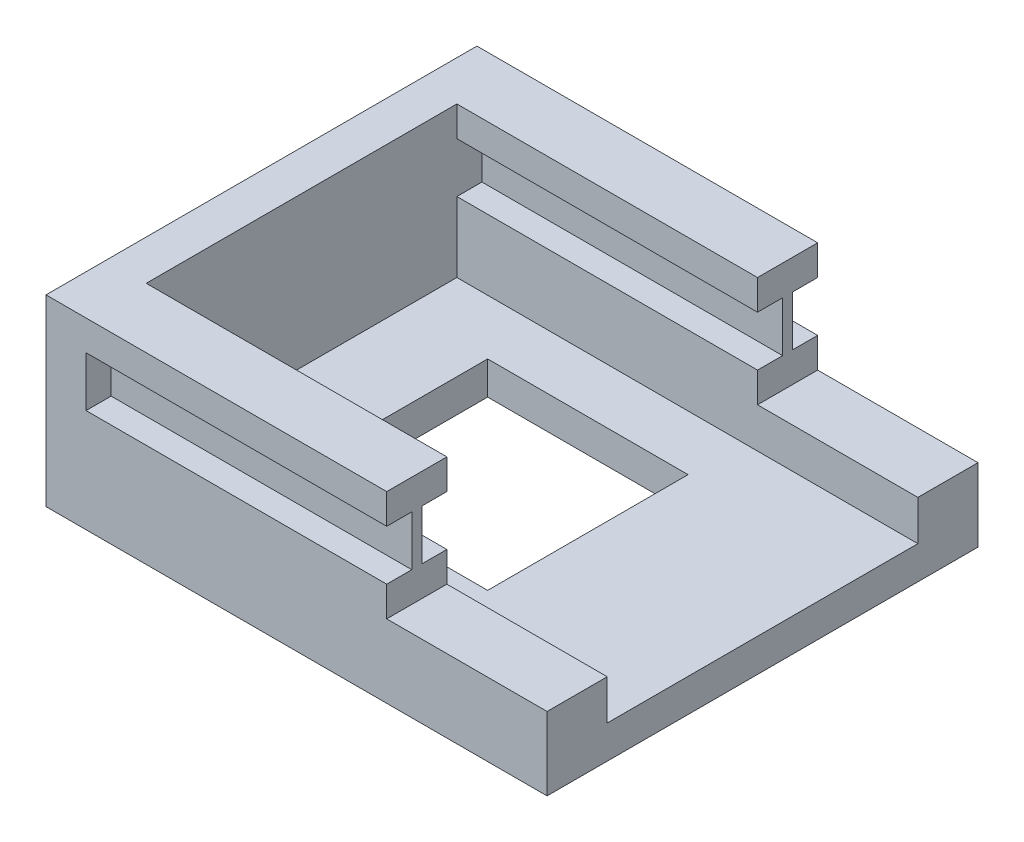
SolidWorks part; units mm, degrees
ref_plane "Front Plane" through (0, 0, 0) normal (0, 0, 1) x (1, 0, 0)
ref_plane "Top Plane" through (0, 0, 0) normal (0, 1, 0) x (1, 0, 0)
ref_plane "Right Plane" through (0, 0, 0) normal (1, 0, 0) x (0, 0, -1)
sketch "Sketch1" plane through (0, 0, 0) normal (0, 0, 1) x (1, 0, 0)
  line L0 (1, 15) -> (5, 15)
  line L1 (1, -3.3) -> (56, -3.3)
  line L2 (1, -3.3) -> (1, 15)
  line L3 (5, 15) -> (5, 4)
  line L4 (5, 4) -> (56, 4)
  line L5 (56, 4) -> (56, -3.3)
  point P1 (0, 0)
  point P4 (0, 0)
  point P8 (0, 0)
  point P9 (0, 0)
  point P10 (0, 0)
  point P11 (0, 0)
  point P12 (0, 0)
  dimension "D1" = 51
  dimension "D2" = 7.3
  dimension "D3" = 11
extrude "Boss-Extrude1" add sketch "Sketch1" along normal blind 43 contours L4 L5 L1 L2 L0 L3
sketch "Sketch3" plane through (0, 0, 43) normal (0, 0, 1) x (1, 0, 0)
  line L0 (56, 4) -> (56, -3.3) construction
  line L1 (5, 4) -> (56, 4)
  line L2 (5, 4) -> (5, 0)
  line L3 (5, 0) -> (56, 0)
  line L4 (56, 4) -> (56, 0)
  dimension "D1" = 4
extrude "Cut-Extrude1" cut sketch "Sketch3" against normal blind 31 from offset 6 offset against normal yes
sketch "Sketch4" plane through (0, 0, 0) normal (0, 1, 0) x (1, 0, 0)
  line L0 (5, -6) -> (5, -37) construction
  line L1 (13.57, -11.5) -> (33.57, -11.5)
  line L2 (13.57, -11.5) -> (13.57, -31.5)
  line L3 (13.57, -31.5) -> (33.57, -31.5)
  line L4 (33.57, -11.5) -> (33.57, -31.5)
  line L5 (13.57, -11.5) -> (33.57, -31.5) construction
  line L6 (13.57, -31.5) -> (33.57, -11.5) construction
  line L7 (1, 0) -> (56, 0) construction
  point P0 (23.57, -21.5)
  dimension "D1" = 20
  dimension "D2" = 20
  dimension "D3" = 8.57
  dimension "D4" = 11.5
extrude "Cut-Extrude2" cut sketch "Sketch4" against normal up to next
fillet "Fillet1" [suppressed] radius 4
fillet "Fillet2" [suppressed] radius 7
sketch "Sketch5" plane through (56, 0, 0) normal (1, 0, 0) x (0, 0, -1)
  line L0 (-6, 4) -> (0, 4) construction
  line L1 (-6, 4) -> (0, 4)
  line L2 (0, 4) -> (0, 7)
  line L3 (-6, 12) -> (-6, 15)
  line L4 (0, 7) -> (-2.5, 7)
  line L5 (-6, 15) -> (0, 15)
  line L6 (-21.5, -3.3) -> (-21.5, 22.0277) construction
  line L7 (-43, -3.3) -> (0, -3.3) construction
  line L8 (-37, 7) -> (-37, 4)
  line L9 (-39.5, 7) -> (-37, 7)
  line L10 (-39.5, 12) -> (-39.5, 7)
  line L11 (-37, 12) -> (-39.5, 12)
  line L12 (-2.5, 7) -> (-2.5, 12)
  line L13 (-2.5, 12) -> (0, 12)
  line L14 (-43, 15) -> (0, 15) construction
  line L15 (0, 15) -> (0, 12)
  line L16 (-43, 15) -> (-43, 12)
  line L17 (-6, 12) -> (-3.5, 12)
  line L18 (-3.5, 12) -> (-3.5, 7)
  line L19 (-3.5, 7) -> (-6, 7)
  line L20 (-6, 7) -> (-6, 4)
  line L21 (-40.5, 12) -> (-43, 12)
  line L22 (-40.5, 7) -> (-40.5, 12)
  line L23 (-37, 15) -> (-43, 15)
  line L24 (-43, 7) -> (-40.5, 7)
  line L25 (-37, 12) -> (-37, 15)
  line L26 (-43, 4) -> (-43, 7)
  line L27 (-37, 4) -> (-43, 4)
  dimension "D2" = 3
  dimension "D3" = 2.5
  dimension "D4" = 2.5
  dimension "D5" = 3
  dimension "D8" = 3
  dimension "D9" = 2.5
  dimension "D10" = 0
extrude "Boss-Extrude2" add sketch "Sketch5" against normal up to surface (30 mm away) from offset 21 up to face at (5, 5.75, 21.5) offset against normal yes
sketch "Sketch6" plane through (0, 0, 0) normal (0, 0, -1) x (-1, 0, 0)
  line L0 (-1, -3.3) -> (-56, -3.3) construction
  line L1 (-56, 4) -> (-51, 4)
  line L2 (-56, 4) -> (-56, -3.3)
  line L3 (-56, -3.3) -> (-51, -3.3)
  line L4 (-51, 4) -> (-51, -3.3)
  dimension "D1" = 5
extrude "Cut-Extrude3" cut sketch "Sketch6" against normal up to next
